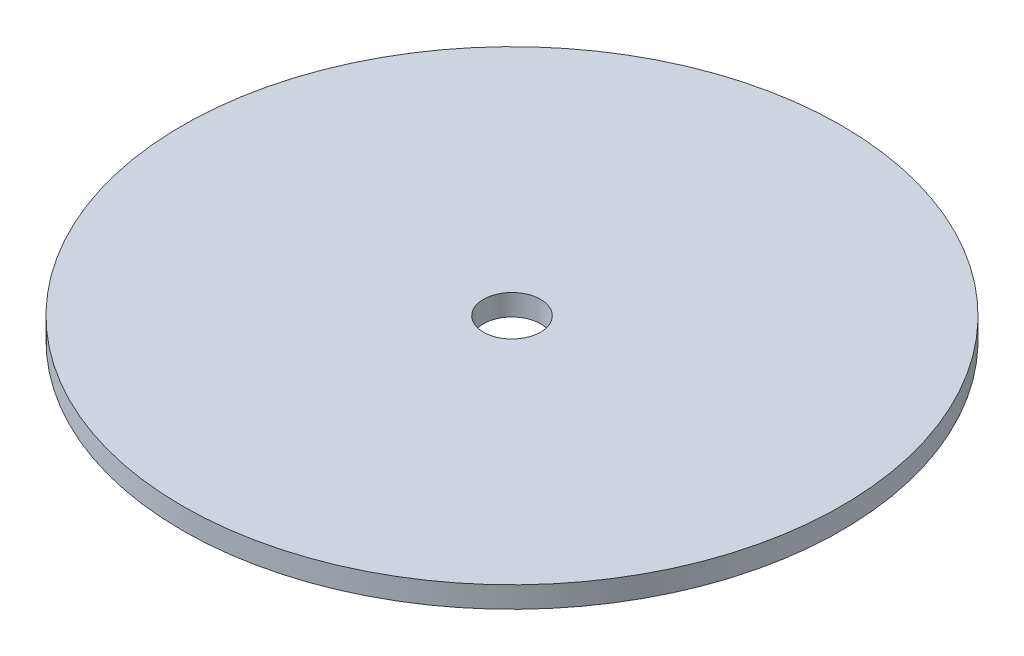
SolidWorks part; units mm, degrees
ref_plane "Front Plane" through (0, 0, 0) normal (0, 0, 1) x (1, 0, 0)
ref_plane "Top Plane" through (0, 0, 0) normal (0, 1, 0) x (1, 0, 0)
ref_plane "Right Plane" through (0, 0, 0) normal (1, 0, 0) x (0, 0, -1)
sketch "Sketch1" plane through (0, 0, 0) normal (0, 1, 0) x (1, 0, 0)
  circle A0 centre (0, 0) radius 50
  dimension "D1" = 100
extrude "Boss-Extrude1" add sketch "Sketch1" along normal blind 3.22
sketch "Sketch2" plane through (0, 3.22, 0) normal (0, 1, 0) x (1, 0, 0)
  circle A0 centre (0, 0) radius 4.325
  dimension "D1" = 8.65
extrude "Cut-Extrude1" cut sketch "Sketch2" against normal blind 4.63
